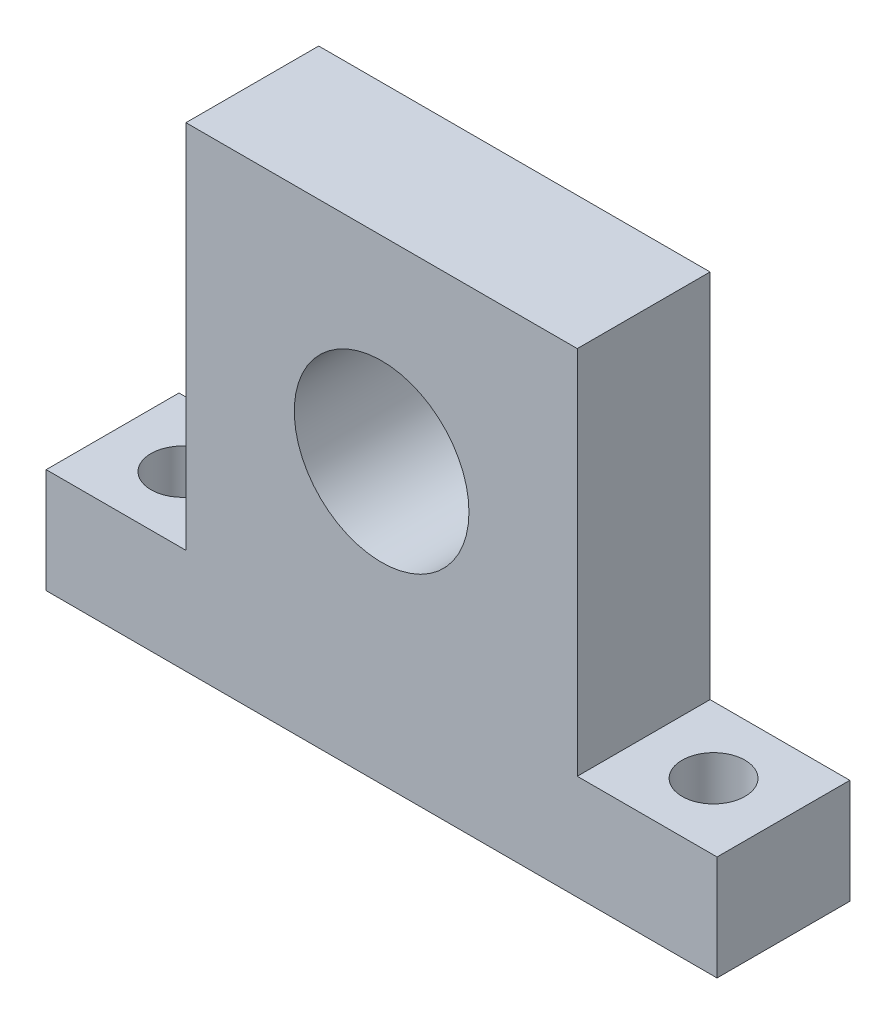
SolidWorks part; units mm, degrees
material "环氧树脂,未充填"
ref_plane "前视基准面" through (0, 0, 0) normal (0, 0, 1) x (1, 0, 0)
ref_plane "上视基准面" through (0, 0, 0) normal (0, 1, 0) x (1, 0, 0)
ref_plane "右视基准面" through (0, 0, 0) normal (1, 0, 0) x (0, 0, -1)
other "Configuration Table"
sketch "草图1" plane through (0, 0, 0) normal (0, 0, 1) x (1, 0, 0)
  line L0 (0, 0) -> (0, 83.6782) construction
  line L1 (-48, -40) -> (-48, -25)
  line L2 (-48, -25) -> (-28, -25)
  line L3 (-28, -25) -> (-28, 28)
  line L4 (-28, 28) -> (28, 28)
  line L5 (-48, -40) -> (48, -40)
  line L6 (48, -40) -> (48, -25)
  line L7 (48, -25) -> (28, -25)
  line L8 (28, -25) -> (28, 28)
  circle A0 centre (0, 0) radius 12.5
  dimension "D6" = 25
  dimension "D1" = 40
  dimension "D2" = 68
  dimension "D3" = 96
  dimension "D4" = 56
  dimension "D5" = 15
extrude "凸台-拉伸1" add sketch "草图1" along normal blind 19
sketch "草图2" plane through (0, -25, 0) normal (0, 1, 0) x (1, 0, 0)
  line L0 (0, 0) -> (0, -35.8722) construction
  line L1 (28, 0) -> (-28, 0) construction
  line L2 (-48, -19) -> (-48, 0) construction
  circle A0 centre (-38, -9.5) radius 4.5
  circle A1 centre (38, -9.5) radius 4.5
  point P10 (-48, -9.5)
  dimension "D1" = 76
  dimension "D2" = 9
extrude "切除-拉伸1" cut sketch "草图2" against normal through all
